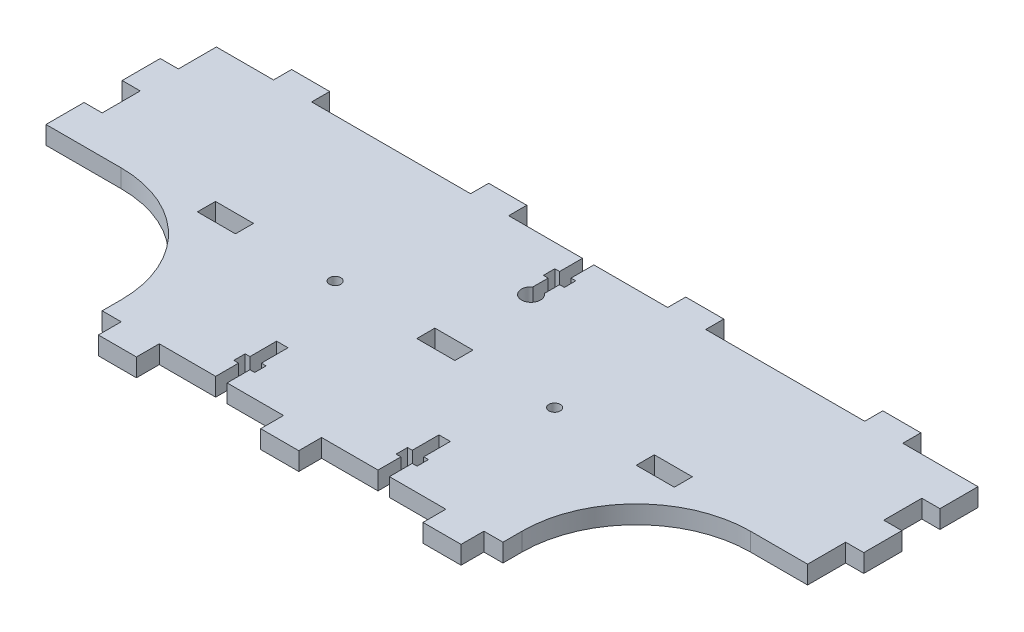
SolidWorks part; units mm, degrees
material "Pine"
ref_plane "Front Plane" through (0, 0, 0) normal (0, 0, 1) x (1, 0, 0)
ref_plane "Top Plane" through (0, 0, 0) normal (0, 1, 0) x (1, 0, 0)
ref_plane "Right Plane" through (0, 0, 0) normal (1, 0, 0) x (0, 0, -1)
sketch "Sketch1" plane through (0, 0, 0) normal (0, 1, 0) x (1, 0, 0)
  line L0 (-135.25, -3) -> (-102.625, -3) construction
  line L1 (0, 0) -> (-195.25, 0)
  line L2 (0, 0) -> (0, 75)
  line L3 (0, 75) -> (-195.25, 75)
  line L4 (-195.25, 0) -> (-195.25, 75)
  line L5 (-145.25, 0) -> (-135.25, 0)
  line L6 (-145.25, 0) -> (-145.25, -6)
  line L7 (-145.25, -6) -> (-135.25, -6)
  line L8 (-135.25, 0) -> (-135.25, -6)
  line L9 (-102.625, 0) -> (-92.625, 0)
  line L10 (-102.625, 0) -> (-102.625, -6)
  line L11 (-102.625, -6) -> (-92.625, -6)
  line L12 (-92.625, 0) -> (-92.625, -6)
  line L13 (-50, 0) -> (-60, 0)
  line L14 (-50, 0) -> (-50, -6)
  line L15 (-50, -6) -> (-60, -6)
  line L16 (-60, 0) -> (-60, -6)
  line L17 (-200, 45) -> (-195.25, 45)
  line L18 (-200, 45) -> (-200, 35)
  line L19 (-200, 35) -> (-195.25, 35)
  line L20 (-195.25, 45) -> (-195.25, 35)
  line L21 (-200, 65) -> (-195.25, 65)
  line L22 (-200, 65) -> (-200, 55)
  line L23 (-200, 55) -> (-195.25, 55)
  line L24 (-195.25, 65) -> (-195.25, 55)
  line L25 (-92.625, -3) -> (-60, -3) construction
  line L26 (-97.625, 75) -> (-97.625, 0) construction
  line L27 (0, 75) -> (4.75, 75)
  line L28 (0, 75) -> (0, 0)
  line L29 (0, 0) -> (4.75, 0)
  line L30 (4.75, 75) -> (4.75, 0)
  line L31 (4.75, 65) -> (0, 65)
  line L32 (4.75, 55) -> (0, 55)
  line L33 (4.75, 45) -> (0, 45)
  line L34 (4.75, 35) -> (0, 35)
  dimension "D1" = 195.25
  dimension "D2" = 75
  dimension "D3" = 6
  dimension "D4" = 10
  dimension "D5" = 50
  dimension "D6" = 50
  dimension "D7" = 10
  dimension "D8" = 4.75
  dimension "D9" = 35
  dimension "D10" = 10
  dimension "D11" = 4.75
extrude "Boss-Extrude1" add sketch "Sketch1" along normal blind 4.75 contours L22 L23 L4 L21 | L4 L1 L2 L28 L3 | L8 L1 L6 L7 | L12 L1 L10 L11 | L1 L16 L15 L14 | L30 L34 L2 L29 | L33 L30 L32 L28 | L31 L30 L27 L28 | L18 L19 L20 L17
sketch "Sketch3" plane through (0, 4.75, 0) normal (0, 1, 0) x (1, 0, 0)
  line L0 (-97.625, -6) -> (-97.625, 75) construction
  line L1 (-195.25, 35) -> (-180.25, 35)
  line L2 (-195.25, 35) -> (-195.25, 0)
  line L3 (-195.25, 0) -> (-150.25, 0)
  line L4 (-150.25, 5) -> (-150.25, 0)
  line L5 (-102.625, -6) -> (-92.625, -6) construction
  line L6 (4.75, 75) -> (-195.25, 75) construction
  line L7 (0, 0) -> (-45, 0)
  line L8 (-45, 5) -> (-45, 0)
  line L9 (0, 35) -> (-15, 35)
  line L10 (0, 35) -> (0, 0)
  line L12 (0, 35) -> (4.75, 35)
  line L13 (0, 35) -> (0, 0)
  line L14 (0, 0) -> (4.75, 0)
  line L15 (4.75, 35) -> (4.75, 0)
  arc A0 (-150.25, 5) -> (-180.25, 35) centre (-180.25, 5) ccw
  arc A1 (-45, 5) -> (-15, 35) centre (-15, 5) cw
  line M13 (-195.25, 35) -> (-195.25, 0)
  line M14 (-195.25, 0) -> (-145.25, 0)
  line M26 (-50, 0) -> (4.75, 0)
  line M27 (4.75, 0) -> (4.75, 35)
  line M28 (4.75, 35) -> (0, 35)
  dimension "D1" = 30
  dimension "D2" = 45
extrude "Cut-Extrude2" cut sketch "Sketch3" against normal blind 4.75 contours L4 A0 L1 M13 M14 | A1 L8 L10 L9 M26 | L10 M28 M26 M27
sketch "Sketch4" plane through (0, 4.75, 0) normal (0, 1, 0) x (1, 0, 0)
  line L0 (-102.625, 0) -> (-135.25, 0) construction
  line L1 (-120.4375, 0) -> (-117.4375, 0)
  line L2 (-120.4375, 0) -> (-120.4375, 16)
  line L3 (-120.4375, 16) -> (-117.4375, 16)
  line L4 (-117.4375, 0) -> (-117.4375, 16)
  line L5 (-60, 0) -> (-92.625, 0) construction
  line L6 (-77.8125, 0) -> (-74.8125, 0)
  line L7 (-77.8125, 0) -> (-77.8125, 16)
  line L8 (-77.8125, 16) -> (-74.8125, 16)
  line L9 (-74.8125, 0) -> (-74.8125, 16)
  line L11 (-121.6875, 9) -> (-116.1875, 9)
  line L12 (-121.6875, 9) -> (-121.6875, 6)
  line L13 (-121.6875, 6) -> (-116.1875, 6)
  line L14 (-116.1875, 9) -> (-116.1875, 6)
  line L15 (-79.0625, 9) -> (-73.5625, 9)
  line L16 (-79.0625, 9) -> (-79.0625, 6)
  line L17 (-79.0625, 6) -> (-73.5625, 6)
  line L18 (-73.5625, 9) -> (-73.5625, 6)
  point P20 (-118.9375, 6)
  point P21 (-118.9375, 16)
  point P22 (-76.3125, 16)
  point P23 (-76.3125, 6)
  point P24 (-118.9375, 0)
  point P25 (-76.3125, 0)
  dimension "D1" = 3
  dimension "D2" = 16
  dimension "D3" = 3
  dimension "D4" = 6
  dimension "D5" = 5.5
extrude "Cut-Extrude3" cut sketch "Sketch4" against normal blind 4.75 contours L12 L13 L14 L11 | L4 L3 L2 L1 | L7 L8 L9 L6 | L17 L18 L15 L16
sketch "Sketch5" plane through (0, 0, 0) normal (0, -1, 0) x (1, 0, 0)
  line L0 (-160.25, -39.75) -> (-150.25, -39.75) construction
  line L1 (-150.25, -39.75) -> (-150.25, -35) construction
  line L2 (-150.25, -35) -> (-160.25, -35) construction
  line L3 (-160.25, -35) -> (-160.25, -39.75) construction
  line L4 (-102.625, -39.75) -> (-92.625, -39.75) construction
  line L5 (-92.625, -39.75) -> (-92.625, -35) construction
  line L6 (-92.625, -35) -> (-102.625, -35) construction
  line L7 (-102.625, -35) -> (-102.625, -39.75) construction
  line L8 (-45, -39.75) -> (-35, -39.75) construction
  line L9 (-35, -39.75) -> (-35, -35) construction
  line L10 (-35, -35) -> (-45, -35) construction
  line L11 (-45, -35) -> (-45, -39.75) construction
  line L12 (-160.25, -39.75) -> (-150.25, -39.75)
  line L13 (-150.25, -39.75) -> (-150.25, -35)
  line L14 (-150.25, -35) -> (-160.25, -35)
  line L15 (-160.25, -35) -> (-160.25, -39.75)
  line L16 (-102.625, -39.75) -> (-92.625, -39.75)
  line L17 (-92.625, -39.75) -> (-92.625, -35)
  line L18 (-92.625, -35) -> (-102.625, -35)
  line L19 (-102.625, -35) -> (-102.625, -39.75)
  line L20 (-45, -39.75) -> (-35, -39.75)
  line L21 (-35, -39.75) -> (-35, -35)
  line L22 (-35, -35) -> (-45, -35)
  line L23 (-45, -35) -> (-45, -39.75)
extrude "Cut-Extrude4" cut sketch "Sketch5" against normal through all
sketch "Sketch6" plane through (0, 0, 0) normal (0, -1, 0) x (1, 0, 0)
  line L0 (-127.9375, -39.75) -> (-124.9375, -39.75) construction
  line L1 (-124.9375, -39.75) -> (-124.9375, -35) construction
  line L2 (-124.9375, -35) -> (-127.9375, -35) construction
  line L3 (-127.9375, -35) -> (-127.9375, -39.75) construction
  line L4 (-70.3125, -39.75) -> (-67.3125, -39.75) construction
  line L5 (-67.3125, -39.75) -> (-67.3125, -35) construction
  line L6 (-67.3125, -35) -> (-70.3125, -35) construction
  line L7 (-70.3125, -35) -> (-70.3125, -39.75) construction
  line L8 (-127.9375, -39.75) -> (-124.9375, -39.75) construction
  line L9 (-124.9375, -39.75) -> (-124.9375, -35) construction
  line L10 (-124.9375, -35) -> (-127.9375, -35) construction
  line L11 (-127.9375, -35) -> (-127.9375, -39.75) construction
  line L12 (-70.3125, -39.75) -> (-67.3125, -39.75) construction
  line L13 (-67.3125, -39.75) -> (-67.3125, -35) construction
  line L14 (-67.3125, -35) -> (-70.3125, -35) construction
  line L15 (-70.3125, -35) -> (-70.3125, -39.75) construction
  circle A0 centre (-68.8125, -37.375) radius 1.5
  circle A1 centre (-126.4375, -37.375) radius 1.5
  point P14 (-68.8125, -39.75)
  point P16 (-126.4375, -39.75)
  point P18 (-124.9375, -37.375)
  dimension "D1" = 3
extrude "Cut-Extrude5" cut sketch "Sketch6" against normal through all
sketch "Sketch7" plane through (0, 4.75, 0) normal (0, 1, 0) x (1, 0, 0)
  line L0 (4.75, 75) -> (-195.25, 75) construction
  line L1 (-180.25, 75) -> (-170.25, 75)
  line L2 (-180.25, 75) -> (-180.25, 79.75)
  line L3 (-180.25, 79.75) -> (-170.25, 79.75)
  line L4 (-170.25, 75) -> (-170.25, 79.75)
  line L5 (-170.25, 77.375) -> (-128.5, 77.375) construction
  line L6 (-128.5, 75) -> (-118.5, 75)
  line L7 (-128.5, 75) -> (-128.5, 79.75)
  line L8 (-128.5, 79.75) -> (-118.5, 79.75)
  line L9 (-118.5, 75) -> (-118.5, 79.75)
  line L10 (-76.75, 75) -> (-66.75, 75)
  line L11 (-76.75, 75) -> (-76.75, 79.75)
  line L12 (-76.75, 79.75) -> (-66.75, 79.75)
  line L13 (-66.75, 75) -> (-66.75, 79.75)
  line L14 (-25, 75) -> (-15, 75)
  line L15 (-25, 75) -> (-25, 79.75)
  line L16 (-25, 79.75) -> (-15, 79.75)
  line L17 (-15, 75) -> (-15, 79.75)
  line L18 (-118.5, 77.375) -> (-76.75, 77.375) construction
  line L19 (-66.75, 77.375) -> (-25, 77.375) construction
  line L20 (-195.25, 65) -> (-195.25, 75) construction
  line L21 (0, 55) -> (0, 65) construction
  dimension "D1" = 4.75
  dimension "D2" = 10
  dimension "D3" = 15
  dimension "D4" = 15
extrude "Boss-Extrude2" add sketch "Sketch7" against normal blind 4.75
sketch "Sketch8" plane through (0, 0, 0) normal (0, -1, 0) x (1, 0, 0)
  line L0 (-76.75, -75) -> (-118.5, -75) construction
  circle A0 centre (-97.625, -60) radius 2.5
  point P5 (-97.625, -75)
  dimension "D1" = 5
  dimension "D2" = 15
extrude "Cut-Extrude6" cut sketch "Sketch8" against normal through all
sketch "Sketch9" plane through (0, 0, 0) normal (0, -1, 0) x (1, 0, 0)
  line L0 (-76.75, -75) -> (-118.5, -75) construction
  line L1 (-99.125, -75) -> (-96.125, -75)
  line L2 (-99.125, -75) -> (-99.125, -59)
  line L3 (-99.125, -59) -> (-96.125, -59)
  line L4 (-96.125, -75) -> (-96.125, -59)
  line L5 (-77.8125, -16) -> (-74.8125, -16) construction
  line L6 (-94.875, -69) -> (-100.375, -69)
  line L7 (-94.875, -69) -> (-94.875, -66)
  line L8 (-94.875, -66) -> (-100.375, -66)
  line L9 (-100.375, -69) -> (-100.375, -66)
  line L10 (-79.0625, -9) -> (-79.0625, -6) construction
  line L11 (-73.5625, -9) -> (-73.5625, -6) construction
  line L12 (-77.8125, -16) -> (-74.8125, -16) construction
  line L13 (-79.0625, -9) -> (-79.0625, -6) construction
  line L14 (-73.5625, -9) -> (-73.5625, -6) construction
  line L15 (-73.5625, -9) -> (-79.0625, -9) construction
  line L16 (-74.8125, -16) -> (-74.8125, 0) construction
  line L17 (-73.5625, -6) -> (-73.5625, 0) construction
  line L18 (-60, 0) -> (-74.8125, 0) construction
  line L19 (-94.875, -69) -> (-94.875, -75) construction
  point P10 (-97.625, -59)
  point P11 (-97.625, -66)
  point P12 (-97.625, -75)
extrude "Cut-Extrude7" cut sketch "Sketch9" against normal blind 10 contours L8 L9 L6 L7 | L2 L3 L4 L1
